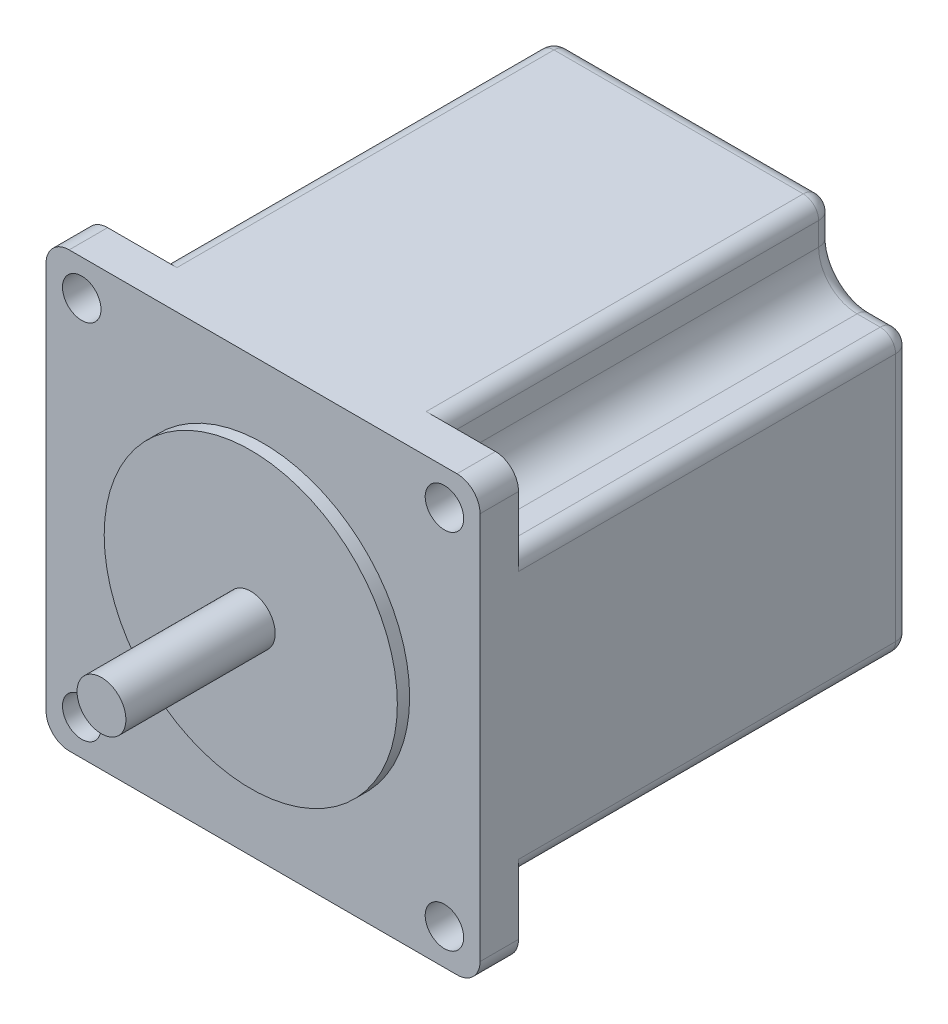
SolidWorks part; units mm, degrees
ref_plane "Front Plane" through (0, 0, 0) normal (0, 0, 1) x (1, 0, 0)
ref_plane "Top Plane" through (0, 0, 0) normal (0, 1, 0) x (1, 0, 0)
ref_plane "Right Plane" through (0, 0, 0) normal (1, 0, 0) x (0, 0, -1)
sketch "Sketch1" plane through (0, 0, 0) normal (0, 0, 1) x (1, 0, 0)
  line L0 (-23.57, 23.57) -> (23.57, 23.57) construction
  line L1 (-25.2, 28.2) -> (25.2, 28.2)
  line L2 (-28.2, 25.2) -> (-28.2, -25.2)
  line L3 (-25.2, -28.2) -> (25.2, -28.2)
  line L4 (28.2, 25.2) -> (28.2, -25.2)
  line L5 (-28.2, 28.2) -> (28.2, -28.2) construction
  line L6 (-28.2, -28.2) -> (28.2, 28.2) construction
  line L7 (23.57, 23.57) -> (23.57, -23.57) construction
  line L8 (23.57, -23.57) -> (-23.57, -23.57) construction
  line L9 (-23.57, -23.57) -> (-23.57, 23.57) construction
  circle A0 centre (23.57, 23.57) radius 2.5
  circle A1 centre (-23.57, 23.57) radius 2.5
  circle A2 centre (-23.57, -23.57) radius 2.5
  circle A3 centre (23.57, -23.57) radius 2.5
  arc A4 (-28.2, -25.2) -> (-25.2, -28.2) centre (-25.2, -25.2) ccw
  arc A5 (25.2, -28.2) -> (28.2, -25.2) centre (25.2, -25.2) ccw
  arc A6 (28.2, 25.2) -> (25.2, 28.2) centre (25.2, 25.2) ccw
  arc A7 (-25.2, 28.2) -> (-28.2, 25.2) centre (-25.2, 25.2) ccw
  point P0 (0, 0)
  dimension "D3" = 5
  dimension "D4" = 3
  dimension "D1" = 56.4
  dimension "D2" = 47.14
extrude "Boss-Extrude2" add sketch "Sketch1" against normal blind 56
ref_plane "Plane1" through (0, 0, -5) normal (0, 0, 1) x (1, 0, 0)
sketch "Sketch2" plane through (0, 0, -5) normal (0, 0, 1) x (1, 0, 0)
  line L0 (18.2, 28.2) -> (18.2, 23.2)
  line L1 (25.2, 28.2) -> (-25.2, 28.2) construction
  line L2 (23.2, 18.2) -> (28.2, 18.2)
  line L3 (28.2, -25.2) -> (28.2, 25.2) construction
  line L4 (25.2, 28.2) -> (18.2, 28.2)
  line L5 (28.2, 18.2) -> (28.2, 25.2)
  line L6 (0, 0) -> (0, 28.2) construction
  line L7 (0, 0) -> (28.2, 0) construction
  line L8 (-28.2, 18.2) -> (-28.2, 25.2)
  line L9 (-25.2, 28.2) -> (-18.2, 28.2)
  line L10 (-23.2, 18.2) -> (-28.2, 18.2)
  line L11 (-18.2, 28.2) -> (-18.2, 23.2)
  line L12 (-18.2, -28.2) -> (-18.2, -23.2)
  line L13 (-23.2, -18.2) -> (-28.2, -18.2)
  line L14 (-25.2, -28.2) -> (-18.2, -28.2)
  line L15 (-28.2, -18.2) -> (-28.2, -25.2)
  line L16 (28.2, -18.2) -> (28.2, -25.2)
  line L17 (25.2, -28.2) -> (18.2, -28.2)
  line L18 (23.2, -18.2) -> (28.2, -18.2)
  line L19 (18.2, -28.2) -> (18.2, -23.2)
  arc A0 (28.2, 25.2) -> (25.2, 28.2) centre (25.2, 25.2) ccw construction
  arc A1 (28.2, 25.2) -> (25.2, 28.2) centre (25.2, 25.2) ccw
  arc A2 (23.2, 18.2) -> (18.2, 23.2) centre (23.2, 23.2) cw
  arc A3 (-23.2, 18.2) -> (-18.2, 23.2) centre (-23.2, 23.2) ccw
  arc A4 (-28.2, 25.2) -> (-25.2, 28.2) centre (-25.2, 25.2) cw
  arc A5 (-28.2, -25.2) -> (-25.2, -28.2) centre (-25.2, -25.2) ccw
  arc A6 (-23.2, -18.2) -> (-18.2, -23.2) centre (-23.2, -23.2) cw
  arc A7 (23.2, -18.2) -> (18.2, -23.2) centre (23.2, -23.2) ccw
  arc A8 (28.2, -25.2) -> (25.2, -28.2) centre (25.2, -25.2) cw
  dimension "D1" = 5
  dimension "D2" = 5
extrude "Cut-Extrude1" cut sketch "Sketch2" against normal through all
sketch "Sketch3" plane through (0, 0, 0) normal (0, 0, 1) x (1, 0, 0)
  circle A0 centre (0, 0) radius 19.05
  dimension "D1" = 38.1
extrude "Boss-Extrude3" add sketch "Sketch3" along normal blind 1.6
sketch "Sketch4" plane through (0, 0, 0) normal (0, 0, 1) x (1, 0, 0)
  circle A0 centre (0, 0) radius 3.175
  dimension "D1" = 6.35
extrude "Boss-Extrude4" add sketch "Sketch4" along normal blind 21
fillet "Fillet1" radius 2 24 edges at (-18.2, -25.7, -56) (0, -28.2, -56) (18.2, -25.7, -56) (19.6645, -19.6645, -56) (25.7, -18.2, -56) (28.2, 0, -56) (25.7, 18.2, -56) (19.6645, 19.6645, -56) (18.2, 25.7, -56) (0, 28.2, -56) (-18.2, 25.7, -56) (-19.6645, 19.6645, -56) (-25.7, 18.2, -56) (-28.2, 0, -56) (-25.7, -18.2, -56) (-19.6645, -19.6645, -56) (-18.2, 28.2, -30.5) (-28.2, 18.2, -30.5) (-28.2, -18.2, -30.5) (-18.2, -28.2, -30.5) (18.2, -28.2, -30.5) (28.2, -18.2, -30.5) (28.2, 18.2, -30.5) (18.2, 28.2, -30.5)
